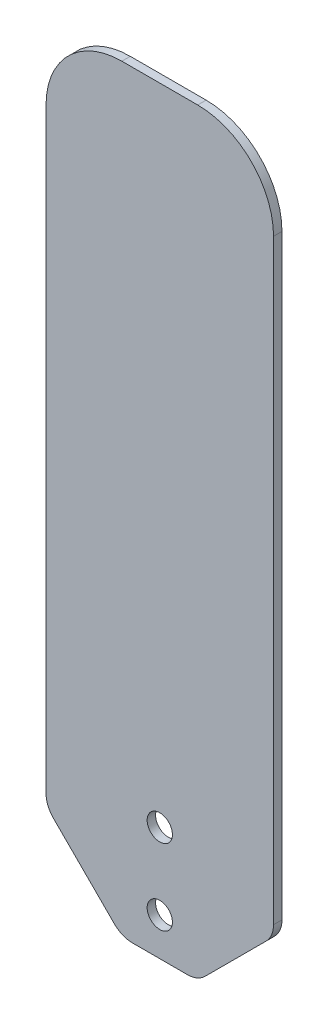
SolidWorks part; units mm, degrees
ref_plane "Alzado" through (0, 0, 0) normal (0, 0, 1) x (1, 0, 0)
ref_plane "Planta" through (0, 0, 0) normal (0, 1, 0) x (1, 0, 0)
ref_plane "Vista lateral" through (0, 0, 0) normal (1, 0, 0) x (0, 0, -1)
sketch "Model" plane through (0, 0, 0) normal (0, 0, 1) x (1, 0, 0)
  line L0 (95.8925, 168.7619) -> (102.4072, 168.7619)
  line L1 (112.6499, 179.0045) -> (112.6499, 249.7619)
  line L2 (103.6499, 258.7619) -> (94.6499, 258.7619)
  line L3 (85.6499, 249.7619) -> (85.6499, 179.0045)
  line L4 (93.7712, 169.6406) -> (86.5286, 176.8832)
  line L5 (104.5286, 169.6406) -> (111.7712, 176.8832)
  circle A0 centre (99.1499, 173.2619) radius 1.5
  arc A1 (112.6499, 249.7619) -> (103.6499, 258.7619) centre (103.6499, 249.7619) ccw
  arc A2 (94.6499, 258.7619) -> (85.6499, 249.7619) centre (94.6499, 249.7619) ccw
  circle A3 centre (99.1499, 182.2619) radius 1.5
  arc A4 (85.6499, 179.0045) -> (86.5286, 176.8832) centre (88.6499, 179.0045) ccw
  arc A5 (111.7712, 176.8832) -> (112.6499, 179.0045) centre (109.6499, 179.0045) ccw
  arc A6 (102.4072, 168.7619) -> (104.5286, 169.6406) centre (102.4072, 171.7619) ccw
  arc A7 (93.7712, 169.6406) -> (95.8925, 168.7619) centre (95.8925, 171.7619) ccw
extrude "Saliente-Extruir1" add sketch "Model" along normal blind 1
